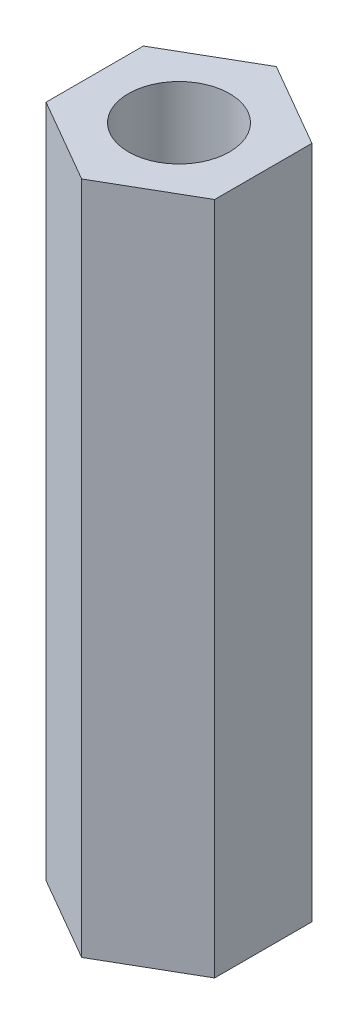
SolidWorks part; units mm, degrees
material "1060 Alloy"
ref_plane "Front Plane" through (0, 0, 0) normal (0, 0, 1) x (1, 0, 0)
ref_plane "Top Plane" through (0, 0, 0) normal (0, 1, 0) x (1, 0, 0)
ref_plane "Right Plane" through (0, 0, 0) normal (1, 0, 0) x (0, 0, -1)
sketch "Sketch1" plane through (0, 0, 0) normal (0, 1, 0) x (1, 0, 0)
  line L1 (0, -2.8868) -> (2.5, -1.4434)
  line L2 (2.5, -1.4434) -> (2.5, 1.4434)
  line L3 (2.5, 1.4434) -> (0, 2.8868)
  line L4 (0, 2.8868) -> (-2.5, 1.4434)
  line L5 (-2.5, 1.4434) -> (-2.5, -1.4434)
  line L6 (-2.5, -1.4434) -> (0, -2.8868)
  circle A1 centre (0, 0) radius 2.5 construction
  circle A2 centre (0, 0) radius 1.5
  dimension "D1" = 5
  dimension "D2" = 3
extrude "Boss-Extrude1" add sketch "Sketch1" along normal blind 20
